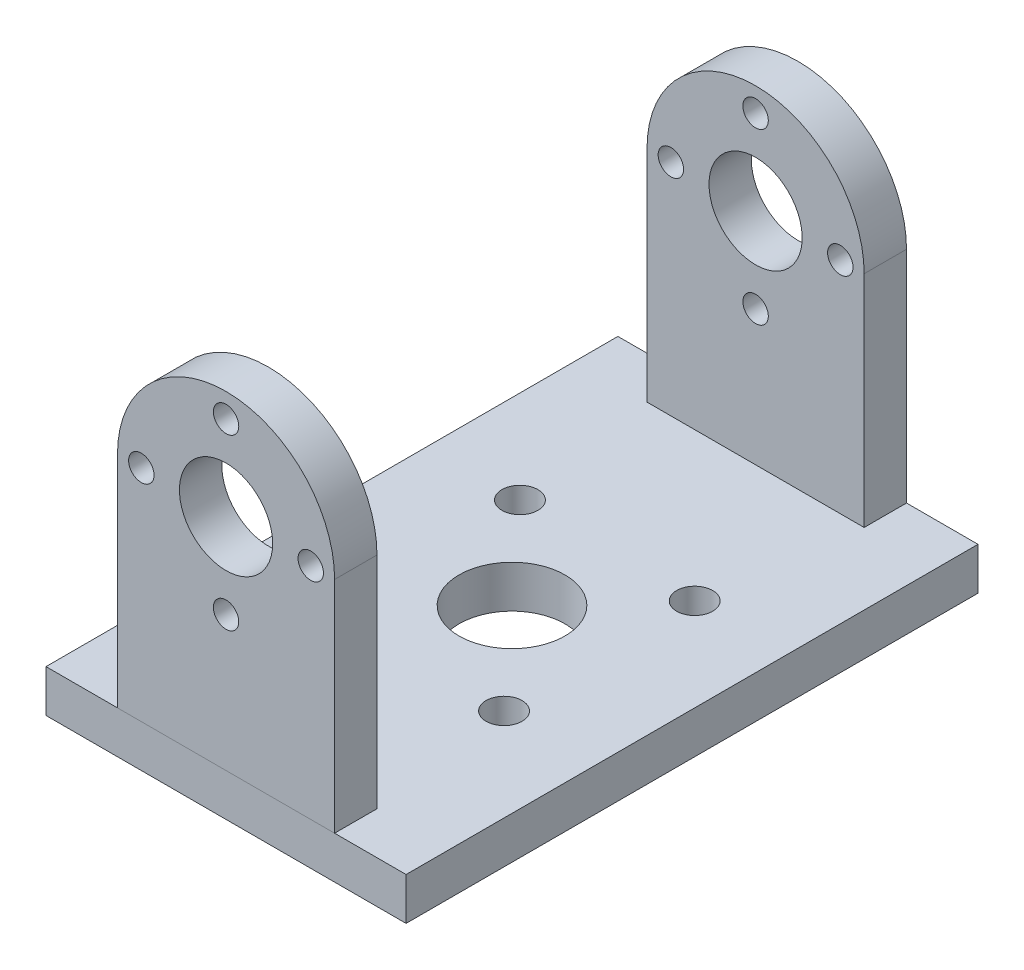
SolidWorks part; units mm, degrees
ref_plane "Front Plane" through (0, 0, 0) normal (0, 0, 1) x (1, 0, 0)
ref_plane "Top Plane" through (0, 0, 0) normal (0, 1, 0) x (1, 0, 0)
ref_plane "Right Plane" through (0, 0, 0) normal (1, 0, 0) x (0, 0, -1)
sketch "Sketch1" plane through (0, 0, 0) normal (0, 0, 1) x (1, 0, 0)
  line L0 (0, 0) -> (0, -68) construction
  line L1 (10.25, 0) -> (10.25, -68)
  line L2 (-10.25, 0) -> (-10.25, -68)
  line L3 (0, 0) -> (0, -68) construction
  line L4 (17, 0) -> (17, -68)
  line L5 (-17, 0) -> (-17, -68)
  line L7 (-10.25, -68) -> (10.25, -68)
  line L8 (-10.25, -68) -> (-10.25, -32.75)
  line L9 (-10.25, -32.75) -> (10.25, -32.75)
  line L10 (10.25, -68) -> (10.25, -32.75)
  line L11 (-17, -32.75) -> (17, -32.75)
  line L12 (-17, -32.75) -> (-17, -28.75)
  line L13 (-17, -28.75) -> (17, -28.75)
  line L14 (17, -32.75) -> (17, -28.75)
  line L15 (-10.25, -68) -> (10.25, -68)
  line L16 (-10.25, -68) -> (-10.25, -79.25)
  line L17 (-10.25, -79.25) -> (10.25, -79.25)
  line L18 (10.25, -68) -> (10.25, -79.25)
  arc A0 (10.25, 0) -> (-10.25, 0) centre (0, 0) ccw
  arc A1 (-10.25, -68) -> (10.25, -68) centre (0, -68) ccw
  arc A2 (17, 0) -> (-17, 0) centre (0, 0) ccw
  arc A3 (-17, -68) -> (17, -68) centre (0, -68) ccw
  circle A4 centre (0, 0) radius 8
  circle A5 centre (0, 8) radius 1.2
  circle A6 centre (8, 0) radius 1.2
  circle A7 centre (0, -8) radius 1.2
  circle A8 centre (-8, 0) radius 1.2
  circle A9 centre (0, -68) radius 10.25
  circle A10 centre (0, 0) radius 4.4
  point P3 (0, -34)
  point P10 (0, -34)
  point P28 (0, 0)
  dimension "D2" = 10.25
  dimension "D3" = 17
  dimension "D4" = 16
  dimension "D5" = 2.4
  dimension "D10" = 8.8
  dimension "D1" = 68
  dimension "D7" = 35.25
  dimension "D8" = 4
  dimension "D9" = 11.25
  dimension "D6" = 4
extrude "Boss-Extrude1" add sketch "Sketch1" along normal blind 4 contours A8 A4 A7 A6 A5 A10 | L1 A0 L2 L13 A8 A4 A5 A6 A7
sketch "Sketch3" plane through (0, -28.75, 0) normal (0, -1, 0) x (-1, 0, 0)
  line L21 (-10.25, -4) -> (-10.25, 0) construction
  line L22 (-17, 0) -> (17, 0)
  line L23 (-17, 0) -> (-17, -46)
  line L24 (-17, -46) -> (17, -46)
  line L25 (17, 0) -> (17, -46)
  line L28 (10.25, 0) -> (-10.25, 0) construction
  circle A0 centre (0, -23) radius 5
  circle A1 centre (-8.25, -14) radius 1.7
  circle A2 centre (8.25, -14) radius 1.7
  circle A3 centre (8.25, -32) radius 1.7
  circle A4 centre (-8.25, -32) radius 1.7
  dimension "D3" = 3.4
  dimension "D4" = 9
  dimension "D5" = 8.25
  dimension "D8" = 23
  dimension "D10" = 8.25
  dimension "D11" = 9
  dimension "D13" = 17
  dimension "D1" = 34
  dimension "D2" = 6.75
  dimension "D9" = 46
  dimension "D12" = 0
  dimension "D6" = 2
  dimension "D7" = 2
extrude "Boss-Extrude3" add sketch "Sketch3" against normal blind 4
ref_plane "Plane1" through (0, 0, 23) normal (0, 0, 1) x (1, 0, 0)
mirror "Mirror1" about plane through (0, 0, 23) normal (0, 0, 1) of "Boss-Extrude1"
sketch "Sketch4" plane through (0, -24.75, 0) normal (0, 1, 0) x (1, 0, 0)
  line L1 (-17, 0) -> (17, 0)
  line L2 (-17, 0) -> (-17, -46)
  line L3 (-17, -46) -> (17, -46)
  line L4 (17, 0) -> (17, -46)
  line L5 (-17, 0) -> (17, -46) construction
  line L6 (-17, -46) -> (17, 0) construction
  line L7 (-10.25, 0) -> (10.25, 0)
  line L8 (-10.25, 0) -> (-10.25, -4)
  line L9 (-10.25, -4) -> (10.25, -4)
  line L10 (10.25, 0) -> (10.25, -4)
  line L11 (-10.25, -42) -> (10.25, -42)
  line L12 (-10.25, -42) -> (-10.25, -46)
  line L13 (-10.25, -46) -> (10.25, -46)
  line L14 (10.25, -42) -> (10.25, -46)
  circle A0 centre (0, -23) radius 5
  circle A1 centre (8.25, -32) radius 1.7
  circle A2 centre (8.25, -14) radius 1.7
  circle A3 centre (-8.25, -14) radius 1.7
  circle A4 centre (-8.25, -32) radius 1.7
  point P0 (0, -23)
  circle M1 centre (0, -23) radius 5
  circle M2 centre (8.25, -14) radius 1.7
  circle M3 centre (-8.25, -14) radius 1.7
  circle M4 centre (-8.25, -32) radius 1.7
  circle M5 centre (8.25, -32) radius 1.7
  line M6 (10.25, -42) -> (10.25, -46)
  line M7 (10.25, -46) -> (17, -46)
  line M8 (17, -46) -> (17, 0)
  line M9 (17, 0) -> (10.25, 0)
  line M10 (10.25, 0) -> (10.25, -4)
  line M11 (10.25, -4) -> (-10.25, -4)
  line M12 (-10.25, -4) -> (-10.25, 0)
  line M13 (-10.25, 0) -> (-17, 0)
  line M14 (-17, 0) -> (-17, -46)
  line M15 (-17, -46) -> (-10.25, -46)
  line M16 (-10.25, -46) -> (-10.25, -42)
  line M17 (-10.25, -42) -> (10.25, -42)
extrude "Boss-Extrude4" add sketch "Sketch4" along normal blind 4 contours M17 M6 M7 M8 M9 M10 M11 M12 M13 M14 M15 M16 M2 M4 M5 M3 M1
sketch "Sketch5" plane through (-17, 0, 0) normal (-1, 0, 0) x (0, 0, 1)
  line L0 (46, -20.75) -> (46, -28.75) construction
  line L1 (0, -28.75) -> (46, -28.75)
  line L2 (0, -28.75) -> (0, -24.75)
  line L3 (0, -24.75) -> (46, -24.75)
  line L4 (46, -28.75) -> (46, -24.75)
extrude "Cut-Extrude1" cut sketch "Sketch5" against normal through all
sketch "Sketch6" plane through (0, -20.75, 0) normal (0, 1, 0) x (1, 0, 0)
  line L2 (-17, 0) -> (17, 0)
  line L3 (-17, 0) -> (-17, 4)
  line L4 (-17, 4) -> (17, 4)
  line L5 (17, 0) -> (17, 4)
  line L6 (-17, -46) -> (17, -46)
  line L7 (-17, -46) -> (-17, -50)
  line L8 (-17, -50) -> (17, -50)
  line L9 (17, -46) -> (17, -50)
  dimension "D1" = 4
  dimension "D2" = 4
extrude "Boss-Extrude5" add sketch "Sketch6" against normal blind 4
ref_plane "Plane3" through (0, 0, 0) normal (0, 0, -1) x (-1, 0, 0)
mirror "Mirror2" about plane through (0, 0, 0) normal (0, 0, -1) of "Boss-Extrude1"
sketch "Sketch7" plane through (0, 0, 46) normal (0, 0, 1) x (1, 0, 0)
  line L1 (10.25, -20.75) -> (-10.25, -20.75)
  line L2 (10.25, -20.75) -> (10.25, 0)
  line L4 (-10.25, -20.75) -> (-10.25, 0)
  arc A0 (10.25, 0) -> (-10.25, 0) centre (0, 0) ccw
  circle A1 centre (0, 0) radius 4.4
  circle A2 centre (8, 0) radius 1.2
  circle A3 centre (0, -8) radius 1.2
  circle A4 centre (-8, 0) radius 1.2
  circle A5 centre (0, 8) radius 1.2
  point P20 (0, 0)
  dimension "D1" = 4
extrude "Boss-Extrude6" add sketch "Sketch7" along normal blind 4 separate body
sketch "Sketch8" plane through (17, 0, 0) normal (1, 0, 0) x (0, 0, -1)
  line L0 (0, -23.2369) -> (0, 23.2369) construction
  line L1 (-46, -20.75) -> (0, -20.75)
  line L2 (-46, -20.75) -> (-46, 10.25)
  line L3 (-46, 10.25) -> (0, 10.25)
  line L4 (0, -20.75) -> (0, 10.25)
  line L5 (-50, -24.75) -> (4, -24.75) construction
  line L6 (4, -28.75) -> (0, -28.75)
  line L7 (4, -28.75) -> (4, -24.75)
  line L8 (4, -24.75) -> (0, -24.75)
  line L9 (0, -28.75) -> (0, -24.75)
extrude "Cut-Extrude2" cut sketch "Sketch8" against normal through all
